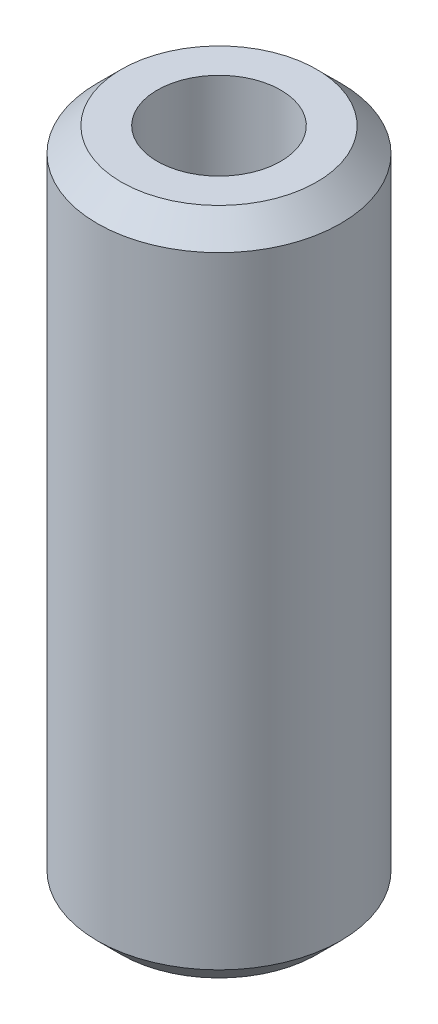
SolidWorks part; units mm, degrees
ref_plane "Front Plane" through (0, 0, 0) normal (0, 0, 1) x (1, 0, 0)
ref_plane "Top Plane" through (0, 0, 0) normal (0, 1, 0) x (1, 0, 0)
ref_plane "Right Plane" through (0, 0, 0) normal (1, 0, 0) x (0, 0, -1)
sketch "Sketch3" plane through (0, 0, 0) normal (0, 1, 0) x (1, 0, 0)
  line L0 (-29.2153, 0) -> (29.7902, 0) construction
  circle A0 centre (0, 0) radius 12.7
  dimension "D1" = 25.4
extrude "Boss-Extrude5" add sketch "Sketch3" along normal blind 69.85
sketch "Sketch6" plane through (0, 0, 0) normal (0, -1, 0) x (1, 0, 0)
  circle A0 centre (0, 0) radius 6.45
  dimension "D1" = 12.9
extrude "Cut-Extrude1" cut sketch "Sketch6" against normal through all contours A0
chamfer "Chamfer1" distance 2.5 angle 45 1 edges at (0, 69.85, 12.7)
chamfer "Chamfer2" distance 2.5 angle 45 1 edges at (0, 0, 12.7)
